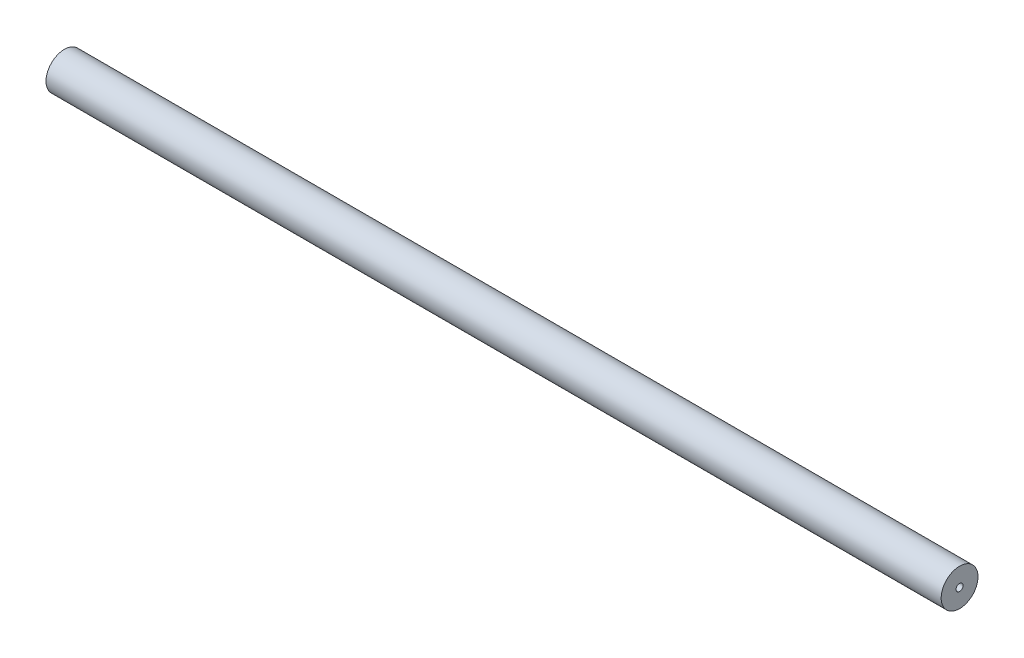
SolidWorks part; units mm, degrees
material "ABS"
ref_plane "Alzado" through (0, 0, 0) normal (0, 0, 1) x (1, 0, 0)
ref_plane "Planta" through (0, 0, 0) normal (0, 1, 0) x (1, 0, 0)
ref_plane "Vista lateral" through (0, 0, 0) normal (1, 0, 0) x (0, 0, -1)
sketch "Sketch2" plane through (0, 0, 0) normal (0, 0, 1) x (1, 0, 0)
  line L0 (-69.1172, 0) -> (69.1172, 0) construction
  line L1 (-300, 12.35) -> (300, 12.35)
  point P3 (0, 12.35)
  point P4 (0, 0)
  point P5 (69.1172, 12.35)
  point P8 (-69.1172, 0)
  point P9 (0, 0)
  point P10 (0, 0)
  dimension "D1" = 24.7
  dimension "D2" = 600
revolve "Revolve-Thin1" add sketch "Sketch2" angle 360 about L0
